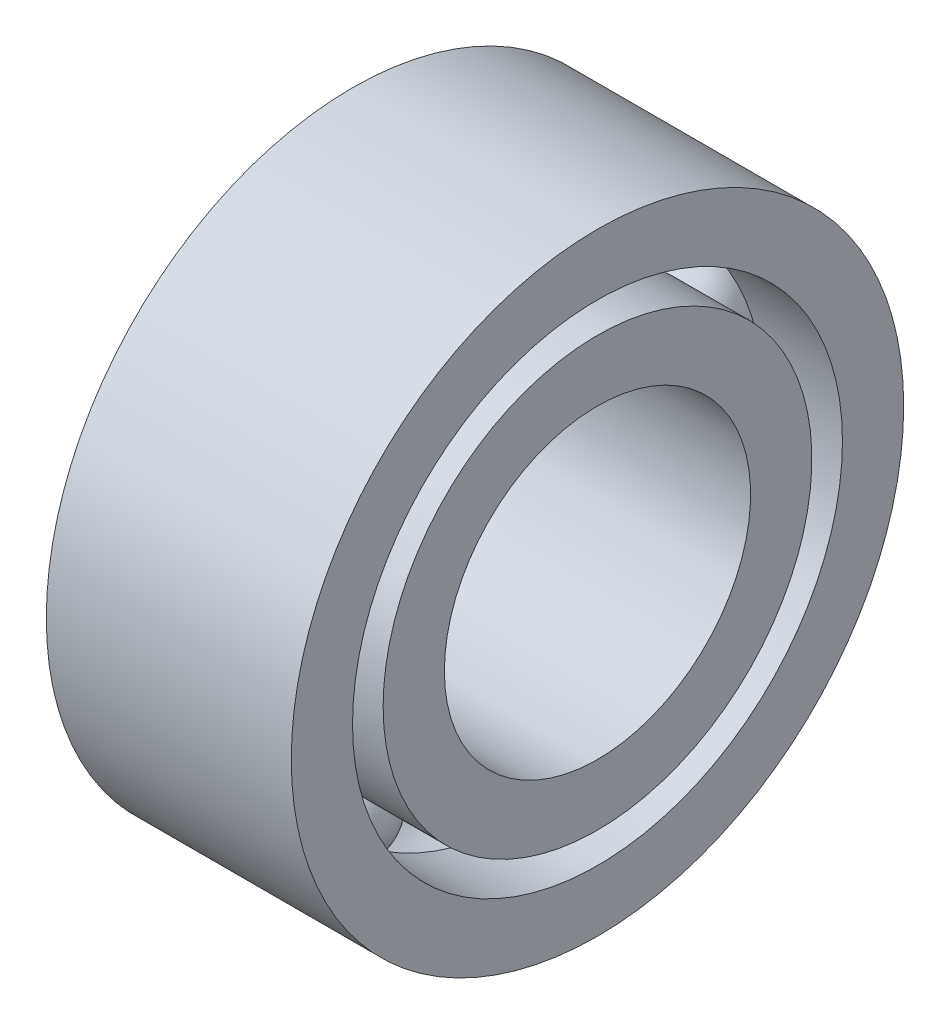
SolidWorks part; units mm, degrees
material "Cast Alloy Steel"
ref_plane "Front" through (0, 0, 0) normal (0, 0, 1) x (1, 0, 0)
ref_plane "Top" through (0, 0, 0) normal (0, 1, 0) x (1, 0, 0)
ref_plane "Right" through (0, 0, 0) normal (1, 0, 0) x (0, 0, -1)
sketch "Sketch1" plane through (0, 0, 0) normal (0, 0, 1) x (1, 0, 0)
  line L0 (-3.6532, 0) -> (4.0378, 0) construction
  line L1 (0, 5) -> (2, 5)
  line L2 (2, 5) -> (2, 4)
  line L3 (2, 4) -> (0.7071, 4)
  line L4 (-2, 4) -> (-2, 5)
  line L5 (-2, 5) -> (0, 5)
  line L6 (0.7071, 3.5) -> (2, 3.5)
  line L7 (2, 3.5) -> (2, 2.5)
  line L8 (2, 2.5) -> (-2, 2.5)
  line L9 (-2, 2.5) -> (-2, 3.5)
  line L10 (-2, 3.5) -> (-0.7071, 3.5)
  line L13 (-0.7071, 4) -> (-2, 4)
  arc A0 (-0.7071, 3.5) -> (0.7071, 3.5) centre (0, 3.75) ccw
  arc A1 (0.7071, 4) -> (-0.7071, 4) centre (0, 3.75) ccw
  dimension "D9" = 1.5
  dimension "D1" = 2
  dimension "D2" = 2
  dimension "D3" = 4
  dimension "D5" = 2.5
  dimension "D6" = 5
  dimension "D7" = 1
  dimension "D8" = 1
revolve "Revolve1" add sketch "Sketch1" angle 360 about L0
sketch "Sketch2" plane through (0, 0, 0) normal (0, 0, 1) x (1, 0, 0)
  line L0 (-0.75, 3.75) -> (0.75, 3.75)
  arc A0 (0.75, 3.75) -> (-0.75, 3.75) centre (0, 3.75) ccw
revolve "Revolve2" add sketch "Sketch2" angle 360 about L0
pattern_circular "CirPattern1" count 10 over 360 about axis through (0, 0, 0) along (1, 0, 0) of bodies 103
